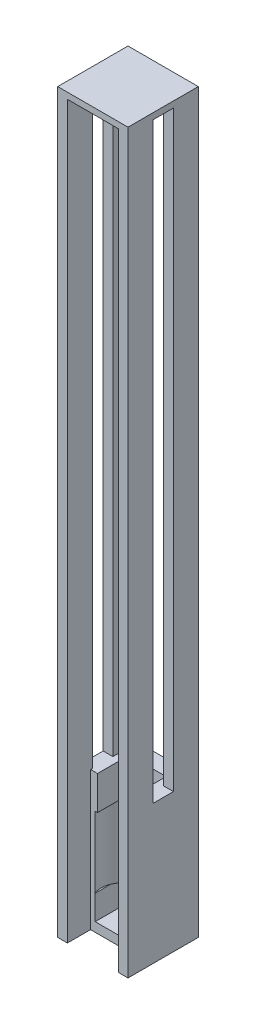
SolidWorks part; units mm, degrees
ref_plane "Front Plane" through (0, 0, 0) normal (0, 0, 1) x (1, 0, 0)
ref_plane "Top Plane" through (0, 0, 0) normal (0, 1, 0) x (1, 0, 0)
ref_plane "Right Plane" through (0, 0, 0) normal (1, 0, 0) x (0, 0, -1)
sketch "Sketch1" plane through (0, 0, 0) normal (0, 1, 0) x (1, 0, 0)
  line L1 (11.3973, -11.3973) -> (-11.3973, -11.3973)
  line L2 (11.3973, -11.3973) -> (11.3973, 11.3973)
  line L3 (11.3973, 11.3973) -> (-11.3973, 11.3973)
  line L4 (-11.3973, -11.3973) -> (-11.3973, 11.3973)
  line L5 (11.3973, -11.3973) -> (-11.3973, 11.3973) construction
  line L6 (11.3973, 11.3973) -> (-11.3973, -11.3973) construction
  point P0 (0, 0)
  point P6 (-11.3973, 11.3973)
extrude "Boss-Extrude1" add sketch "Sketch1" along normal mid plane 45 contours L4 L3 L2 L1
sketch "Sketch2" plane through (0, 0, 0) normal (0, 1, 0) x (1, 0, 0)
  line L0 (0, 0) -> (0, -1.5) construction
  circle A0 centre (0, -1.5) radius 7.25
  circle A1 centre (0, -1.5) radius 5.5542
extrude "Cut-Extrude1" cut sketch "Sketch2" along normal mid plane 23 contours A0
sketch "Sketch4" plane through (0, 0, 11.3973) normal (0, 0, 1) x (1, 0, 0)
  line L0 (11.3973, -22.5) -> (-11.3973, -22.5) construction
  line L1 (8.2557, 22.5) -> (-8.2557, 22.5)
  line L2 (8.2557, 22.5) -> (8.2557, -22.5)
  line L3 (8.2557, -22.5) -> (-8.2557, -22.5)
  line L4 (-8.2557, 22.5) -> (-8.2557, -22.5)
  line L5 (8.2557, 22.5) -> (-8.2557, -22.5) construction
  line L6 (8.2557, -22.5) -> (-8.2557, 22.5) construction
  point P0 (0, 0)
extrude "Cut-Extrude2" cut sketch "Sketch4" against normal mid plane 15 contours L4 L3 L2 L1
sketch "Sketch6" plane through (0, 22.5, 0) normal (0, 1, 0) x (1, 0, 0)
  line L0 (-11.3973, -11.3973) -> (-11.3973, 11.3973) construction
  line L1 (-8.2557, 11.3973) -> (-11.3973, 11.3973)
  line L2 (-8.2557, 11.3973) -> (-8.2557, 3.3396)
  line L3 (-8.2557, 3.3396) -> (-11.3973, 3.3396)
  line L4 (-11.3973, 11.3973) -> (-11.3973, 3.3396)
  line L5 (-8.2557, 11.3973) -> (-11.3973, 3.3396) construction
  line L6 (-8.2557, 3.3396) -> (-11.3973, 11.3973) construction
  line L7 (11.3973, 11.3973) -> (-11.3973, 11.3973) construction
  line L8 (0, 0) -> (0, 11.3973) construction
  line L9 (8.2557, 3.3396) -> (11.3973, 3.3396)
  line L10 (11.3973, 11.3973) -> (11.3973, 3.3396)
  line L11 (8.2557, 11.3973) -> (11.3973, 11.3973)
  line L12 (8.2557, 11.3973) -> (8.2557, 3.3396)
  line L13 (-8.2557, -3.8973) -> (-8.2557, -11.3973) construction
  line L14 (-8.2557, -3.3396) -> (-11.3973, -3.3396)
  line L15 (-8.2557, -3.3396) -> (-8.2557, -11.3973)
  line L16 (-8.2557, -11.3973) -> (-11.3973, -11.3973)
  line L17 (-11.3973, -3.3396) -> (-11.3973, -11.3973)
  line L18 (-8.2557, -3.3396) -> (-11.3973, -11.3973) construction
  line L19 (-8.2557, -11.3973) -> (-11.3973, -3.3396) construction
  line L20 (8.2557, -3.3396) -> (8.2557, -11.3973)
  line L21 (11.3973, -3.3396) -> (11.3973, -11.3973)
  line L22 (8.2557, -11.3973) -> (11.3973, -11.3973)
  line L23 (8.2557, -3.3396) -> (11.3973, -3.3396)
  point P0 (-9.8265, 7.3684)
  point P16 (-9.8265, -7.3684)
extrude "Boss-Extrude2" add sketch "Sketch6" along normal blind 192
sketch "Sketch8" plane through (0, 214.5, 0) normal (0, 1, 0) x (1, 0, 0)
  line L1 (-11.3973, 11.3973) -> (11.3973, 11.3973)
  line L2 (-11.3973, 11.3973) -> (-11.3973, -11.3973)
  line L3 (-11.3973, -11.3973) -> (11.3973, -11.3973)
  line L4 (11.3973, 11.3973) -> (11.3973, -11.3973)
extrude "Boss-Extrude3" add sketch "Sketch8" along normal blind 2
sketch "Sketch10" plane through (0, 11.5, 0) normal (0, -1, 0) x (1, 0, 0)
  line L1 (6, 6.375) -> (-6, 6.375)
  line L2 (6, 6.375) -> (6, -6.375)
  line L3 (6, -6.375) -> (-6, -6.375)
  line L4 (-6, 6.375) -> (-6, -6.375)
  line L5 (6, 6.375) -> (-6, -6.375) construction
  line L6 (6, -6.375) -> (-6, 6.375) construction
  point P0 (0, 0)
  point P7 (0, 0)
  point P9 (0, 0)
  point P10 (0, 0)
  point P11 (0, 0)
  point P12 (0, 0)
extrude "Cut-Extrude4" cut sketch "Sketch10" against normal up to surface (11 mm away) up to face at (0, 22.5, -1.25)
sketch "Sketch11" plane through (0, -11.5, 0) normal (0, 1, 0) x (1, 0, 0)
  line L1 (6.75, 5.25) -> (-6.75, 5.25)
  line L2 (6.75, 5.25) -> (6.75, -8.25)
  line L3 (6.75, -8.25) -> (-6.75, -8.25)
  line L4 (-6.75, 5.25) -> (-6.75, -8.25)
  line L5 (6.75, 5.25) -> (-6.75, -8.25) construction
  line L6 (6.75, -8.25) -> (-6.75, 5.25) construction
  point P0 (0, -1.5)
extrude "Cut-Extrude5" cut sketch "Sketch11" against normal blind 8
